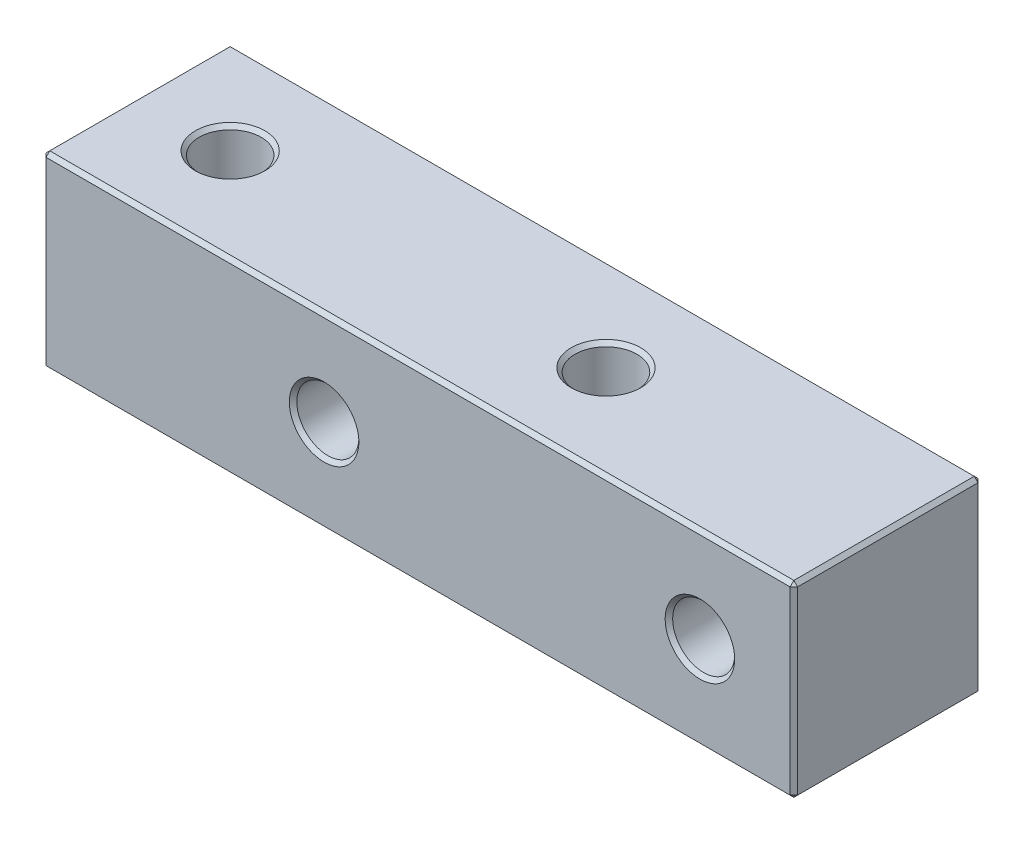
SolidWorks part; units mm, degrees
ref_plane "前视基准面" through (0, 0, 0) normal (0, 0, 1) x (1, 0, 0)
ref_plane "上视基准面" through (0, 0, 0) normal (0, 1, 0) x (1, 0, 0)
ref_plane "右视基准面" through (0, 0, 0) normal (1, 0, 0) x (0, 0, -1)
sketch "草图1" plane through (0, 0, 0) normal (0, 1, 0) x (1, 0, 0)
  line L1 (-20, 5) -> (20, 5)
  line L2 (-20, 5) -> (-20, -5)
  line L3 (-20, -5) -> (20, -5)
  line L4 (20, 5) -> (20, -5)
  line L5 (-20, 5) -> (20, -5) construction
  line L6 (-20, -5) -> (20, 5) construction
  point P0 (0, 0)
  dimension "D1" = 10
  dimension "D2" = 40
extrude "凸台-拉伸1" add sketch "草图1" along normal mid plane 10
hole_wizard "M4 螺纹孔1" positions "草图4" profile "草图6" tap size "M4" standard "GB" end condition through all
sketch "草图4" plane through (0, 5, 0) normal (0, 1, 0) x (1, 0, 0)
  line L0 (-20, 5) -> (-20, -5) construction
  line L1 (0, 0) -> (-50000, 0) construction
  point P0 (-15, 0)
  point P2 (5, 0)
  dimension "D1" = 5
  dimension "D2" = 20
sketch "草图6" plane through (-15, 5, 0) normal (1, 0, 0) x (0, 0, 1)
  line L0 (0, 0) -> (0, 10)
  line L1 (0, 10) -> (1.65, 10)
  line L2 (1.65, 10) -> (1.65, 0)
  line L5 (1.65, 0) -> (0, 0)
  line L11 (0, -6.35) -> (0, 107.95) construction
  dimension "通孔螺纹孔钻头直径" = 3.3
  dimension "通孔螺纹孔钻头深度" = 10
cosmetic thread "孔螺蚊线1"
cosmetic thread "孔螺蚊线5"
hole_wizard "M4 螺纹孔2" positions "草图7" profile "草图8" tap size "M4" standard "GB" end condition through all
sketch "草图7" plane through (0, 0, -5) normal (0, 0, -1) x (-1, 0, 0)
  line L0 (0, 0) -> (-50000, 0) construction
  line L1 (-20, 5) -> (-20, -5) construction
  point P0 (-15, 0)
  point P2 (5, 0)
  dimension "D1" = 5
  dimension "D2" = 20
sketch "草图8" plane through (15, 0, -5) normal (1, 0, 0) x (0, 1, 0)
  line L0 (0, 0) -> (0, 10)
  line L1 (0, 10) -> (1.65, 10)
  line L2 (1.65, 10) -> (1.65, 0)
  line L5 (1.65, 0) -> (0, 0)
  line L11 (0, -6.35) -> (0, 107.95) construction
  dimension "通孔螺纹孔钻头直径" = 3.3
  dimension "通孔螺纹孔钻头深度" = 10
cosmetic thread "孔螺蚊线3"
cosmetic thread "孔螺蚊线4"
chamfer "倒角1" distance 0.2 angle 45 20 edges at (5, -5, 1.65) (-15, -5, 1.65) (-6.65, 0, 5) (13.35, 0, 5) (5, 5, 1.65) (-15, 5, 1.65) (-20, -5, 0) (20, -5, 0) (-20, 0, 5) (0, -5, 5) (20, 0, 5) (0, 5, 5) (-20, 5, 0) (20, 5, 0) (20, 0, -5) (0, 5, -5) (-20, 0, -5) (0, -5, -5) (-6.65, 0, -5) (13.35, 0, -5)
